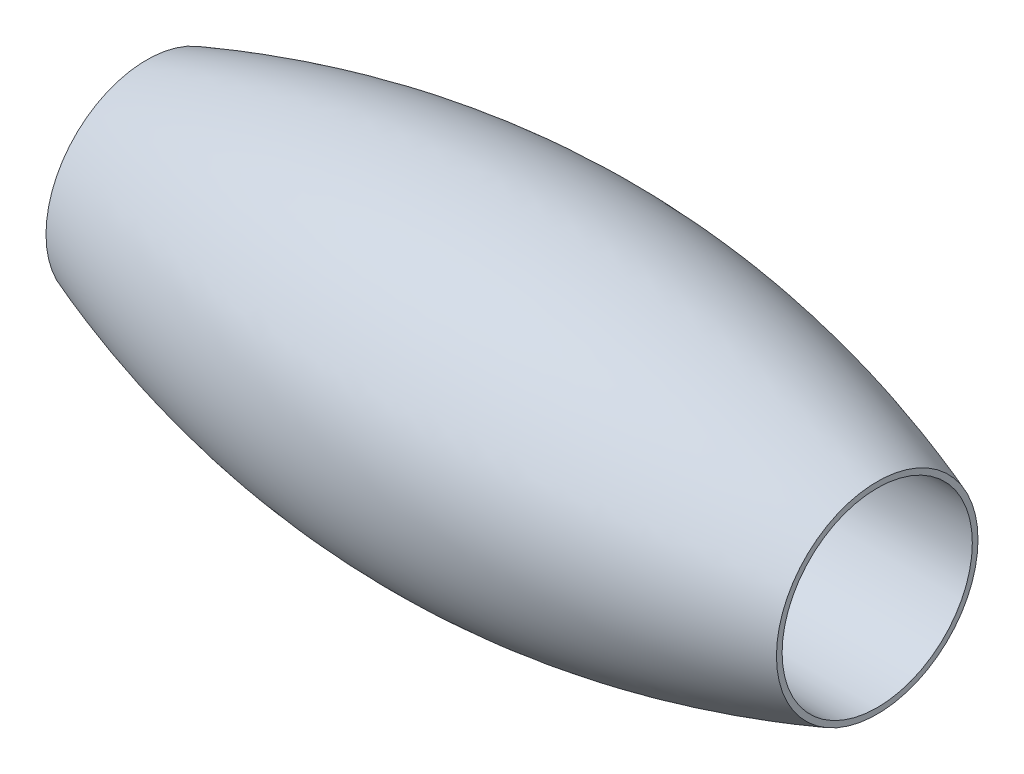
SolidWorks part; units mm, degrees
ref_plane "Front Plane" through (0, 0, 0) normal (0, 0, 1) x (1, 0, 0)
ref_plane "Top Plane" through (0, 0, 0) normal (0, 1, 0) x (1, 0, 0)
ref_plane "Right Plane" through (0, 0, 0) normal (1, 0, 0) x (0, 0, -1)
sketch "Sketch1" plane through (0, 0, 0) normal (0, 0, 1) x (1, 0, 0)
  line L0 (0, 0) -> (12.7, 0)
  line L1 (12.7, 0) -> (12.7, 1.5875)
  line L2 (12.7, 1.5875) -> (0, 1.5875)
  line L3 (6.35, 0) -> (6.35, 2.794) construction
  line L4 (6.35, 0) -> (0.254, 0)
  line L5 (0.254, 0) -> (0.254, 1.6821)
  line L6 (6.35, 0) -> (12.446, 0)
  line L7 (12.446, 0) -> (12.446, 1.6821)
  spline S0 degree 2 poles (0, 1.5875) (6.35, 4.0005) (12.7, 1.5875) knots 0 0 0 1 1 1
  dimension "D1" = 12.7
  dimension "D2" = 1.5875
  dimension "D3" = 2.794
  dimension "D4" = 6.096
  dimension "D5" = 6.096
revolve "Revolve1" add sketch "Sketch1" angle 360 about L0
